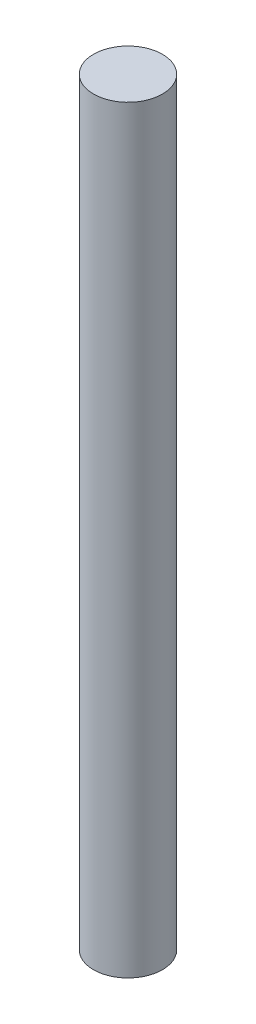
SolidWorks part; units mm, degrees
material "1060 Alloy"
ref_plane "Front Plane" through (0, 0, 0) normal (0, 0, 1) x (1, 0, 0)
ref_plane "Top Plane" through (0, 0, 0) normal (0, 1, 0) x (1, 0, 0)
ref_plane "Right Plane" through (0, 0, 0) normal (1, 0, 0) x (0, 0, -1)
sketch "Sketch1" plane through (0, 0, 0) normal (0, 1, 0) x (1, 0, 0)
  circle A0 centre (0, 0) radius 1.5
  dimension "D1" = 3
extrude "Boss-Extrude1" add sketch "Sketch1" along normal mid plane 33
